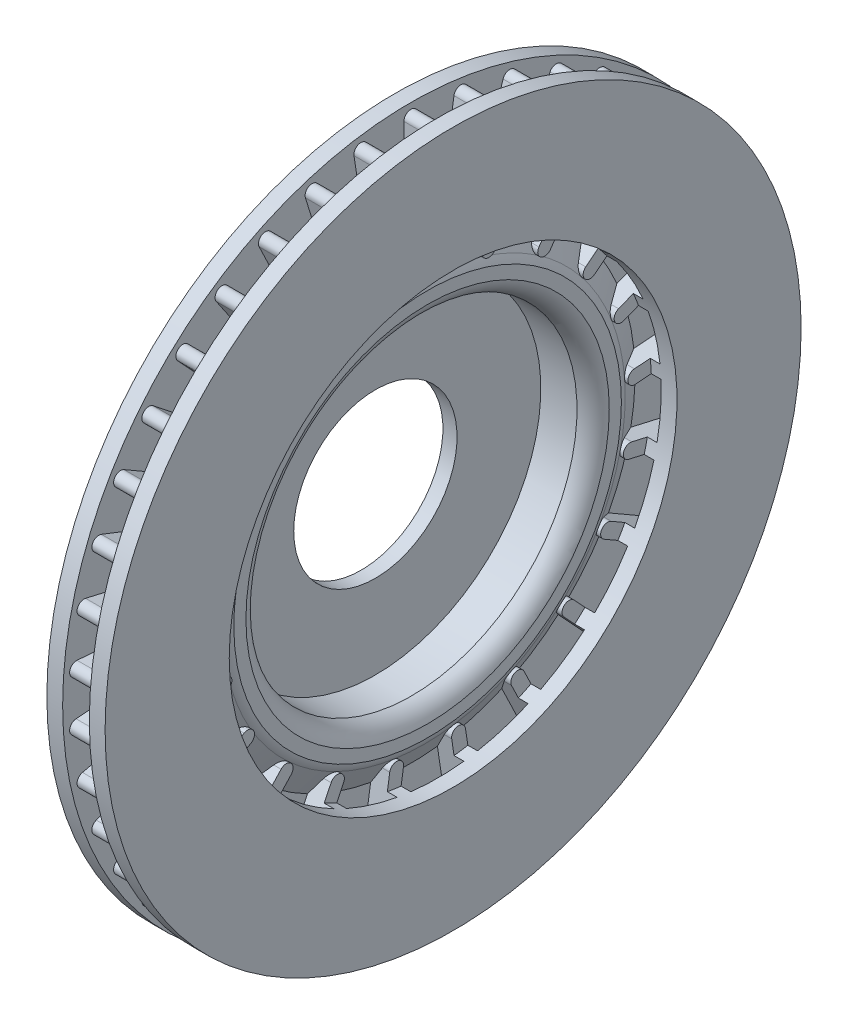
SolidWorks part; units mm, degrees
material "Dökme Alaşımlı Çelik"
ref_plane "Ön Düzlem" through (0, 0, 0) normal (0, 0, 1) x (1, 0, 0)
ref_plane "Üst Düzlem" through (0, 0, 0) normal (0, 1, 0) x (1, 0, 0)
ref_plane "Sağ Düzlem" through (0, 0, 0) normal (1, 0, 0) x (0, 0, -1)
sketch "Çizim1" plane through (0, 0, 0) normal (0, 0, 1) x (1, 0, 0)
  line L0 (0, 96.6) -> (0, 150.1)
  line L1 (0, 150.1) -> (6.8, 150.1)
  line L2 (6.8, 150.1) -> (6.8, 96.6)
  line L3 (6.8, 96.6) -> (12.5735, 86.6)
  line L4 (0, 96.6) -> (5.7735, 86.6)
  line L5 (0, 76.9) -> (5, 76.9)
  line L6 (0, 76.9) -> (0, 75.9)
  line L7 (0, 75.9) -> (7.1, 75.9)
  line L8 (7.1, 75.9) -> (7.1, 71.3)
  line L9 (-91.1403, 0) -> (91.5004, 0) construction
  arc A0 (7.1, 71.3) -> (12.5735, 86.6) centre (4.3475, 80.9137) ccw
  arc A1 (5, 76.9) -> (5.7735, 86.6) centre (-3.3222, 82.4445) ccw
  point P2 (2.8868, 91.6)
  dimension "D13" = 10
  dimension "D14" = 10
  dimension "D1" = 71.3
  dimension "D2" = 4.6
  dimension "D3" = 1
  dimension "D4" = 5
  dimension "D5" = 7.1
  dimension "D6" = 6.8
  dimension "D7" = 53.5
  dimension "D8" = 53.5
  dimension "D9" = 10
  dimension "D10" = 10
  dimension "D11" = 30
  dimension "D12" = 19.7
revolve "Döndür1" add sketch "Çizim1" angle 360 about L9
sketch "Çizim2" plane through (6.8, 0, 0) normal (1, 0, 0) x (0, 0, -1)
  line L0 (0, 0) -> (0, 150.1) construction
  line L1 (0, 0) -> (22.3675, 148.4241) construction
  line L2 (0, 89.6) -> (0, 144.5) construction
  line L3 (-3, 89.6) -> (-3, 144.5)
  line L4 (3, 89.6) -> (3, 144.5)
  line L5 (21.533, 142.8866) -> (17.7655, 117.8866) construction
  line L6 (24.4995, 142.4395) -> (20.732, 117.4395)
  line L7 (18.5665, 143.3336) -> (14.799, 118.3336)
  circle A0 centre (0, 0) radius 150.1 construction
  circle A1 centre (0, 0) radius 147.5
  circle A2 centre (0, 0) radius 80.65
  arc A3 (-3, 89.6) -> (3, 89.6) centre (0, 89.6) ccw
  arc A4 (3, 144.5) -> (-3, 144.5) centre (0, 144.5) ccw
  arc A5 (24.4995, 142.4395) -> (18.5665, 143.3336) centre (21.533, 142.8866) ccw
  arc A6 (14.799, 118.3336) -> (20.732, 117.4395) centre (17.7655, 117.8866) ccw
  circle A7 centre (0, 0) radius 86.6 construction
  point P10 (0, 117.05)
  point P16 (19.6493, 130.3866)
  point P23 (0, 147.5)
  point P26 (0, 86.6)
  point P27 (21.9801, 145.8531)
  circle M2 centre (0, 0) radius 96.6
  dimension "D2" = 295
  dimension "D3" = 161.3
  dimension "D1" = 8.57
  dimension "D4" = 25
  dimension "D5" = 6
  dimension "D6" = 6
extrude "Yükseklik-Ekstrüzyon1" add sketch "Çizim2" along normal blind 11.4 contours L7 A6 L6 A5 | L4 A4 L3 M2 | L3 A3 L4 M2
pattern_circular "Dairesel Kaplama1" count 21 over 360 about axis through (0, 0, 0) along (1, 0, 0) of "Yükseklik-Ekstrüzyon1"
sketch "Çizim3" plane through (0, 0, 0) normal (0, 0, 1) x (1, 0, 0)
  line L0 (18.2, 84.7351) -> (18.2, 137.196) construction
  line L5 (18.2, 150) -> (25, 150)
  line L6 (18.2, 150) -> (18.2, 78.9)
  line L7 (18.2, 78.9) -> (25, 78.9)
  line L8 (25, 150) -> (25, 78.9)
  line L9 (-94.4711, 0) -> (183.2774, 0) construction
  dimension "D1" = 78.9
  dimension "D2" = 71.1
  dimension "D3" = 6.8
revolve "Döndür2" add sketch "Çizim3" angle 360 about L9
sketch "Çizim4" plane through (0, 0, 0) normal (0, 0, 1) x (1, 0, 0)
  line L5 (0, 150.1) -> (0, -150.1) construction
  line L6 (14, 0) -> (37.4, 0)
  line L7 (14, 0) -> (14, 96.5)
  line L8 (14, 96.5) -> (37.4, 96.5)
  line L9 (37.4, 0) -> (37.4, 96.5)
  line L10 (-57.6004, 0) -> (104.5844, 0) construction
  dimension "D1" = 96.5
  dimension "D2" = 23.4
  dimension "D3" = 14
revolve "Kes-Döndür1" cut sketch "Çizim4" angle 360 about L10
sketch "Çizim5" plane through (0, 0, 0) normal (0, 0, 1) x (1, 0, 0)
  line L0 (-62.0815, 0) -> (100.6418, 0) construction
  line L1 (-14.6, 35.2) -> (-14.6, 76.9)
  line L2 (-14.6, 76.9) -> (0, 76.9)
  line L3 (0, 150.1) -> (0, -150.1) construction
  line L4 (0, 76.9) -> (0, 75.9)
  line L5 (0, 75.9) -> (7.1, 75.9)
  line L6 (7.1, 75.9) -> (7.1, 71.3)
  line L7 (7.1, 71.3) -> (-8.5, 71.3)
  line L8 (-8.5, 71.3) -> (-8.5, 35.2)
  line L9 (-14.6, 35.2) -> (-8.5, 35.2)
  dimension "D1" = 35.2
  dimension "D2" = 41.7
  dimension "D3" = 5.6
  dimension "D4" = 4.6
  dimension "D5" = 7.1
  dimension "D6" = 6.1
  dimension "D7" = 8.5
revolve "Döndür6" add sketch "Çizim5" angle 360 about L0
